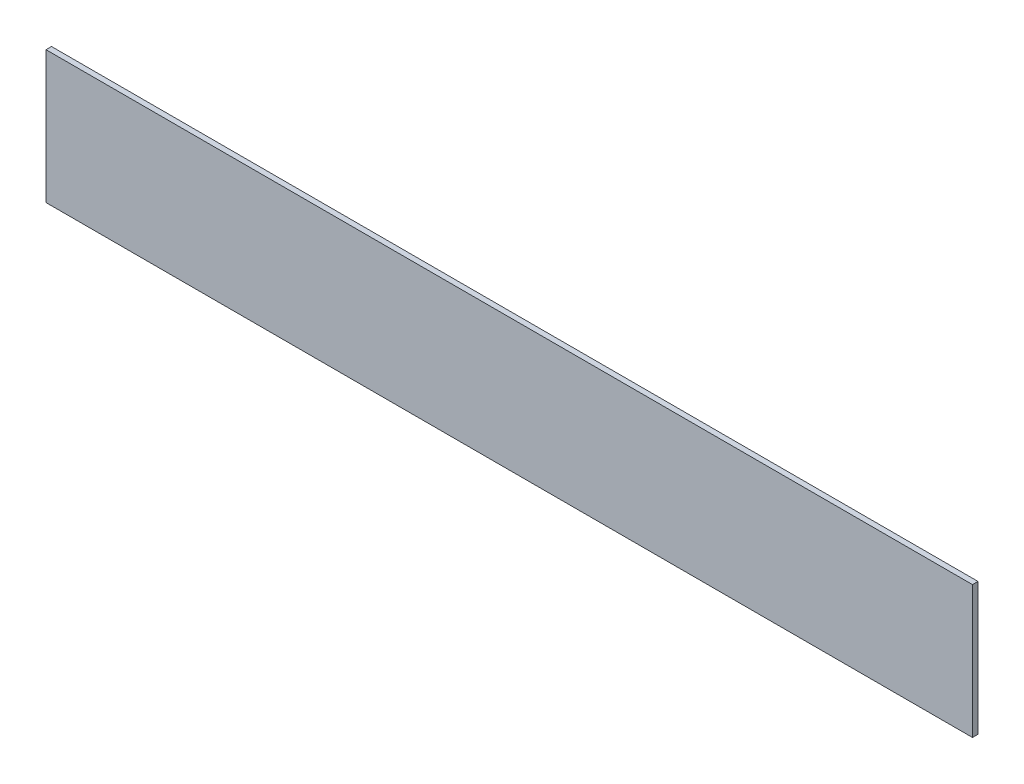
SolidWorks part; units mm, degrees
material "6061-T6 (SS)"
ref_plane "Front Plane" through (0, 0, 0) normal (0, 0, 1) x (1, 0, 0)
ref_plane "Top Plane" through (0, 0, 0) normal (0, 1, 0) x (1, 0, 0)
ref_plane "Right Plane" through (0, 0, 0) normal (1, 0, 0) x (0, 0, -1)
sketch "Sketch1" plane through (0, -330.2, 0) normal (0, 0, 1) x (1, 0, 0)
  line L1 (-247.2046, 6612.1072) -> (285.9414, 6612.1072)
  line L2 (-247.2046, 6612.1072) -> (-247.2046, 6535.9072)
  line L3 (-247.2046, 6535.9072) -> (285.9414, 6535.9072)
  line L4 (285.9414, 6612.1072) -> (285.9414, 6535.9072)
  point P4 (142.875, 6454.7154)
  point P5 (-142.875, 6436.738)
  point P6 (-142.875, 6431.1588)
  point P9 (142.875, 6431.1588)
  point P12 (0, 0)
  dimension "D1" = 76.2
  dimension "D2" = 533.146
extrude "Boss-Extrude1" add sketch "Sketch1" along normal blind 3.175
sketch "Sketch2" plane through (0, 0, 0) normal (0, 0, -1) x (-1, 0, 0)
  line L0 (-285.9414, 6281.9072) -> (247.2046, 6281.9072) construction
  line L1 (215.4546, 6281.9072) -> (171.0046, 6281.9072)
  line L2 (215.4546, 6281.9072) -> (215.4546, 6205.7072)
  line L3 (215.4546, 6205.7072) -> (171.0046, 6205.7072)
  line L4 (171.0046, 6281.9072) -> (171.0046, 6205.7072)
  line L5 (247.2046, 6205.7072) -> (-285.9414, 6205.7072) construction
  line L6 (247.2046, 6281.9072) -> (247.2046, 6205.7072) construction
  line L7 (-19.3684, 6281.9072) -> (-19.3684, 6205.7072) construction
  line L8 (-209.7414, 6281.9072) -> (-209.7414, 6205.7072)
  line L9 (-254.1914, 6205.7072) -> (-209.7414, 6205.7072)
  line L10 (-254.1914, 6281.9072) -> (-254.1914, 6205.7072)
  line L11 (-254.1914, 6281.9072) -> (-209.7414, 6281.9072)
  dimension "D1" = 44.45
  dimension "D2" = 31.75
split line "Split Line1" [suppressed]
